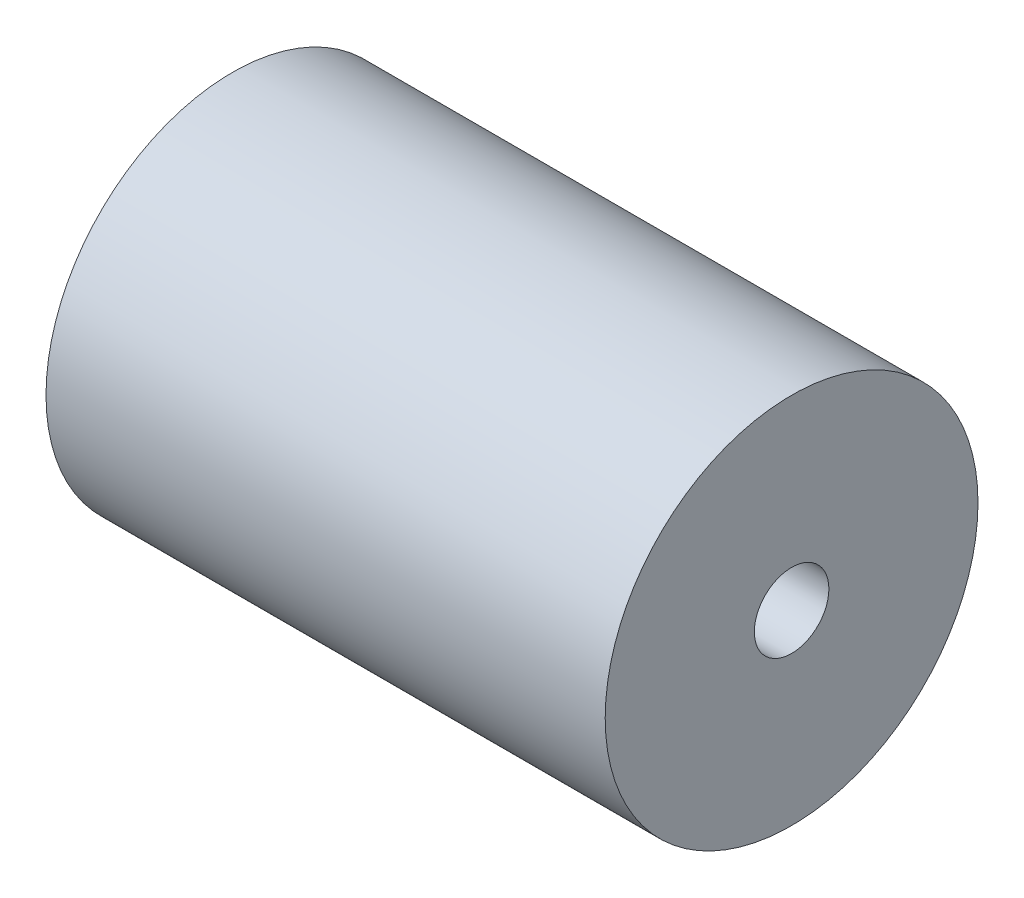
SolidWorks part; units mm, degrees
ref_plane "Front Plane" through (0, 0, 0) normal (0, 0, 1) x (1, 0, 0)
ref_plane "Top Plane" through (0, 0, 0) normal (0, 1, 0) x (1, 0, 0)
ref_plane "Right Plane" through (0, 0, 0) normal (1, 0, 0) x (0, 0, -1)
sketch "Sketch1" plane through (0, 0, 0) normal (1, 0, 0) x (0, 0, -1)
  circle A0 centre (0, 0) radius 5
  point P3 (0, 0)
  dimension "D1" = 10
extrude "Boss-Extrude1" add sketch "Sketch1" along normal blind 15
sketch "Sketch2" plane through (15, 0, 0) normal (1, 0, 0) x (0, 0, -1)
  circle A0 centre (0, 0) radius 1
  dimension "D1" = 2
extrude "Cut-Extrude1" cut sketch "Sketch2" against normal blind 10
